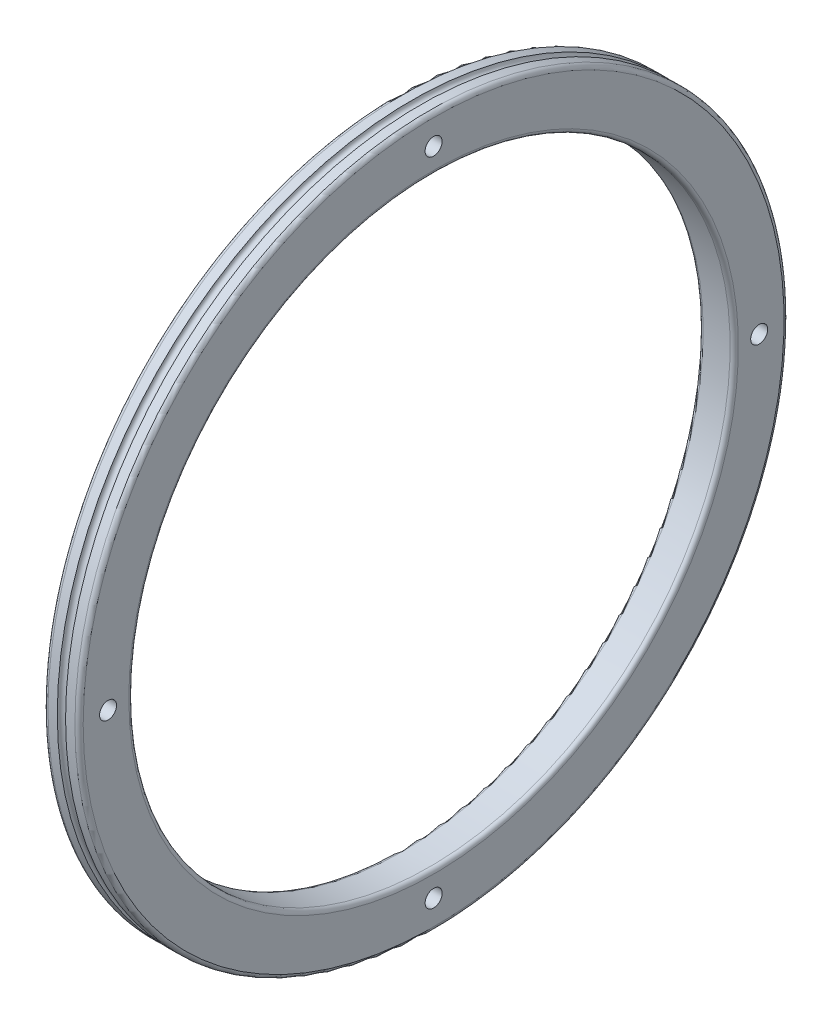
SolidWorks part; units mm, degrees
ref_plane "Front Plane" through (0, 0, 0) normal (0, 0, 1) x (1, 0, 0)
ref_plane "Top Plane" through (0, 0, 0) normal (0, 1, 0) x (1, 0, 0)
ref_plane "Right Plane" through (0, 0, 0) normal (1, 0, 0) x (0, 0, -1)
sketch "Sketch1" plane through (0, 0, 0) normal (0, 1, 0) x (1, 0, 0)
  line L0 (0, 85.4538) -> (0, 0) construction
  line L1 (-4.25, 85.5) -> (-0.9989, 85.5)
  line L2 (4.25, 85.5) -> (4.25, 72.5)
  line L3 (4.25, 72.5) -> (-4.25, 72.5)
  line L4 (-4.25, 72.5) -> (-4.25, 85.5)
  line L5 (0.9989, 85.5) -> (4.25, 85.5)
  line L6 (-9.3632, 0) -> (13.7437, 0) construction
  arc A0 (-0.9989, 85.5) -> (0.9989, 85.5) centre (0, 85.4538) ccw
  point P5 (0, 72.5)
  dimension "D1" = 2
  dimension "D2" = 13
  dimension "D3" = 8.5
  dimension "D4" = 3.2511
  dimension "D5" = 72.5
revolve "Revolve1" add sketch "Sketch1" angle 360 about L6
fillet "Fillet1" radius 1 4 edges at (-4.25, 0, 85.5) (4.25, 0, 85.5) (-4.25, 0, 72.5) (4.25, 0, 72.5)
sketch "Sketch3" plane through (4.25, 0, 0) normal (1, 0, 0) x (0, 0, -1)
  circle A0 centre (-78.5, 0) radius 2.05
  circle A1 centre (0, 78.5) radius 2.05
  circle A2 centre (78.5, 0) radius 2.05
  circle A3 centre (0, -78.5) radius 2.05
  point P12 (0, 0)
  dimension "D2" = 4.1
  dimension "D1" = 78.5
  dimension "D3" = 4
extrude "Cut-Extrude1" cut sketch "Sketch3" against normal up to next
